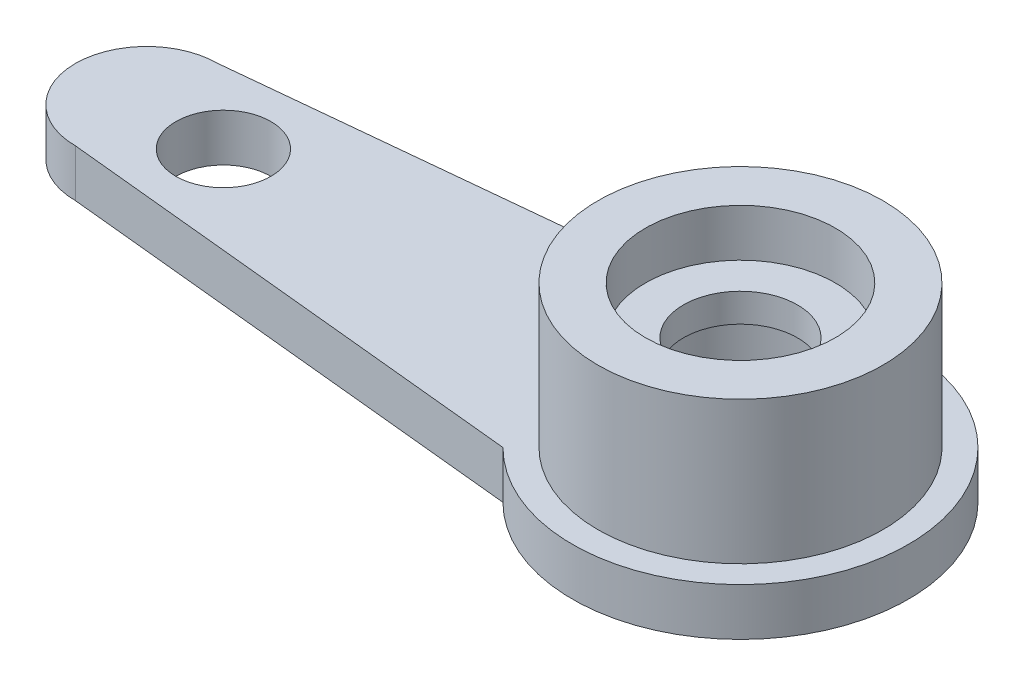
SolidWorks part; units mm, degrees
material "Plain Carbon Steel"
ref_plane "Front Plane" through (0, 0, 0) normal (0, 0, 1) x (1, 0, 0)
ref_plane "Top Plane" through (0, 0, 0) normal (0, 1, 0) x (1, 0, 0)
ref_plane "Right Plane" through (0, 0, 0) normal (1, 0, 0) x (0, 0, -1)
sketch "Sketch1" plane through (0, 0, 0) normal (0, 1, 0) x (1, 0, 0)
  line L0 (0, 82.722) -> (0, -84.0509) construction
  line L1 (-29.5673, 0) -> (39.866, 0) construction
  line L2 (-12.5, 12.5) -> (12.5, 12.5) construction
  line L3 (12.5, 12.5) -> (12.5, 26.25) construction
  line L4 (12.5, 26.25) -> (-12.5, 26.25) construction
  line L5 (-12.5, 26.25) -> (-12.5, 12.5) construction
  line L6 (12.5, -26.25) -> (-12.5, -26.25) construction
  line L7 (-12.5, -12.5) -> (12.5, -12.5) construction
  line L8 (-12.5, -26.25) -> (-12.5, -12.5) construction
  line L9 (12.5, -12.5) -> (12.5, -26.25) construction
  line L10 (-62.5, -7.5) -> (-62.5, 7.5) construction
  line L11 (-12.5, 12.5) -> (-62.5, 7.5)
  line L12 (-62.5, -7.5) -> (-12.5, -12.5)
  line L13 (62.5, 7.5) -> (62.5, -7.5) construction
  line L14 (12.5, 12.5) -> (62.5, 7.5) construction
  line L15 (62.5, -7.5) -> (12.5, -12.5) construction
  circle A0 centre (0, 0) radius 10
  arc A1 (12.5, 26.25) -> (-12.5, 26.25) centre (0, 26.25) ccw construction
  arc A2 (-12.5, -26.25) -> (12.5, -26.25) centre (0, -26.25) ccw construction
  arc A3 (-62.5, -7.5) -> (-62.5, 7.5) centre (-62.5, 0) cw
  arc A4 (62.5, 7.5) -> (62.5, -7.5) centre (62.5, 0) cw construction
  arc A8 (-12.5, 12.5) -> (-12.5, -12.5) centre (0, 0) cw
  point P7 (12.5, 19.375)
  point P10 (0, 12.5)
  point P18 (0, -12.5)
  point P23 (-62.5, 0)
  point P28 (62.5, 0)
  dimension "D1" = 20
  dimension "D2" = 12.5
  dimension "D3" = 25
  dimension "D4" = 26.25
  dimension "D5" = 15
  dimension "D6" = 62.5
  dimension "D7" = 62.5
extrude "Boss-Extrude1" add sketch "Sketch1" along normal mid plane 5
sketch "Sketch2" plane through (0, 2.5, 0) normal (0, 1, 0) x (1, 0, 0)
  circle A0 centre (0, 0) radius 15
  circle A3 centre (0, 0) radius 10
  dimension "D1" = 30
  dimension "D2" = 20
extrude "Boss-Extrude2" add sketch "Sketch2" along normal blind 15
sketch "Sketch3" plane through (0, 2.5, 0) normal (0, 1, 0) x (1, 0, 0)
  line L0 (-79.2105, 0) -> (78.9841, 0) construction
  circle A0 centre (30.5828, 0) radius 5 construction
  circle A1 centre (-54.4172, 0) radius 5
  dimension "D1" = 10
  dimension "D2" = 85
extrude "Cut-Extrude1" cut sketch "Sketch3" against normal through all
sketch "Sketch4" plane through (0, 0, 0) normal (0, 1, 0) x (1, 0, 0)
  circle A0 centre (0, 0) radius 10
  circle A1 centre (0, 0) radius 10 construction
  circle A2 centre (0, 0) radius 6
  dimension "D1" = 12
extrude "Boss-Extrude3" add sketch "Sketch4" along normal blind 3 from offset 9.5
